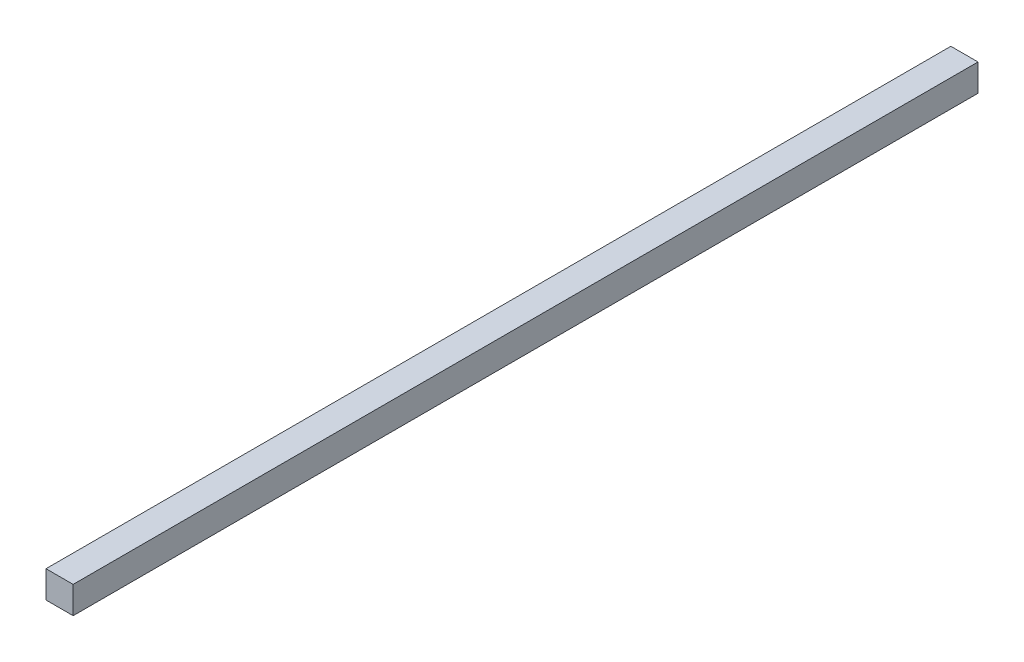
SolidWorks part; units mm, degrees
ref_plane "前视基准面" through (0, 0, 0) normal (0, 0, 1) x (1, 0, 0)
ref_plane "上视基准面" through (0, 0, 0) normal (0, 1, 0) x (1, 0, 0)
ref_plane "右视基准面" through (0, 0, 0) normal (1, 0, 0) x (0, 0, -1)
sketch "草图1" plane through (0, 0, 0) normal (0, 0, 1) x (1, 0, 0)
  line L1 (-15, 15) -> (15, 15)
  line L2 (-15, 15) -> (-15, -15)
  line L3 (-15, -15) -> (15, -15)
  line L4 (15, 15) -> (15, -15)
  line L5 (-15, 15) -> (15, -15) construction
  line L6 (-15, -15) -> (15, 15) construction
  point P0 (0, 0)
  dimension "D1" = 30
  dimension "D2" = 30
extrude "凸台-拉伸1" add sketch "草图1" along normal blind 1000
